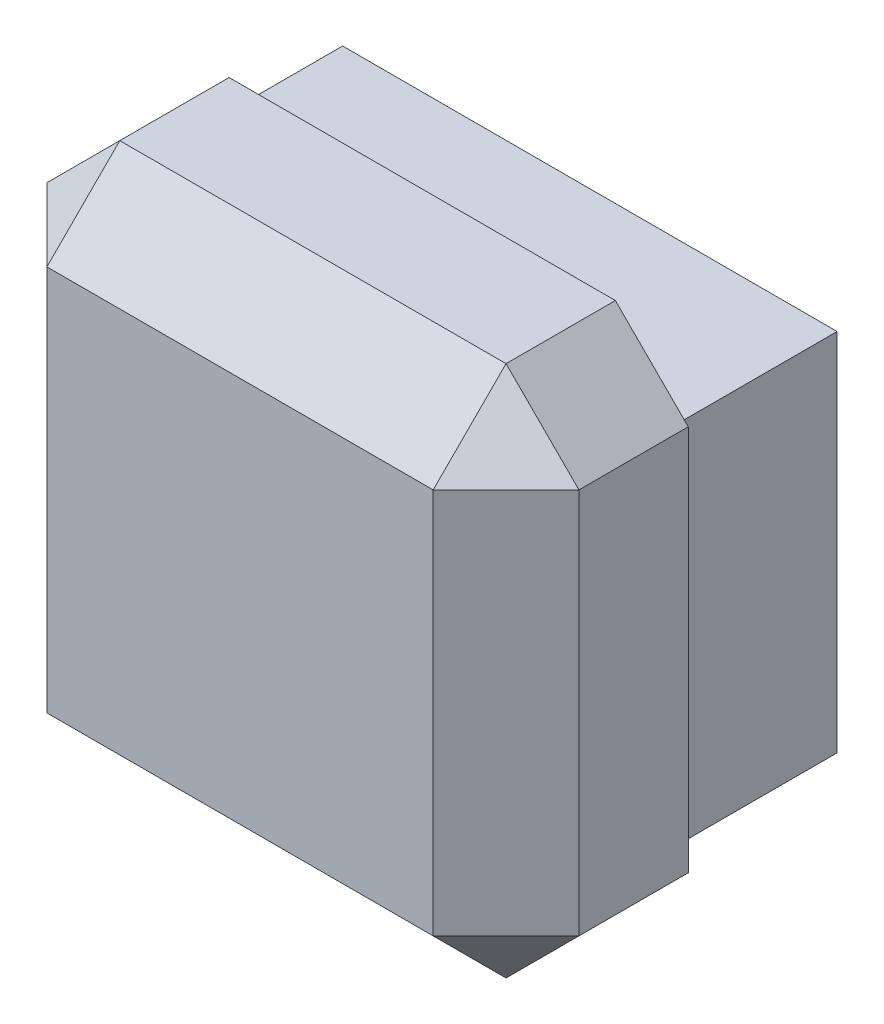
SolidWorks part; units mm, degrees
ref_plane "Front" through (0, 0, 0) normal (0, 0, 1) x (1, 0, 0)
ref_plane "Top" through (0, 0, 0) normal (0, 1, 0) x (1, 0, 0)
ref_plane "Right" through (0, 0, 0) normal (1, 0, 0) x (0, 0, -1)
sketch "Sketch1" plane through (0, 0, 0) normal (0, 0, 1) x (1, 0, 0)
  line L1 (-1.8923, -1.0033) -> (1.8923, -1.0033) construction
  line L2 (-1.8923, -1.0033) -> (-1.8923, 1.0033) construction
  line L3 (-1.8923, 1.0033) -> (1.8923, 1.0033) construction
  line L4 (1.8923, -1.0033) -> (1.8923, 1.0033) construction
  line L5 (-3.3923, -2.5033) -> (3.3923, -2.5033)
  line L6 (-3.3923, -2.5033) -> (-3.3923, 2.5033)
  line L7 (-3.3923, 2.5033) -> (3.3923, 2.5033)
  line L8 (3.3923, -2.5033) -> (3.3923, 2.5033)
  line L9 (-3.3923, -2.5033) -> (3.3923, 2.5033) construction
  line L10 (-3.3923, 2.5033) -> (3.3923, -2.5033) construction
  line L11 (-1.9423, -1.0533) -> (1.9423, -1.0533)
  line L12 (-1.9423, -1.0533) -> (-1.9423, 1.0533)
  line L13 (-1.9423, 1.0533) -> (1.9423, 1.0533)
  line L14 (1.9423, -1.0533) -> (1.9423, 1.0533)
  line L15 (-1.9423, -1.0533) -> (1.9423, 1.0533) construction
  line L16 (-1.9423, 1.0533) -> (1.9423, -1.0533) construction
  point P6 (0, 0)
  point P12 (0, 0)
  dimension "D1" = 1.5
  dimension "D2" = 1.5
  dimension "D3" = 0.05
  dimension "D4" = 0.05
extrude "Boss-Extrude1" add sketch "Sketch1" against normal blind 2.3
sketch "Sketch2" plane through (0, 0, 0) normal (0, 0, 1) x (1, 0, 0)
  line L1 (-3.65, -3.65) -> (3.65, -3.65)
  line L2 (-3.65, -3.65) -> (-3.65, 3.65)
  line L3 (-3.65, 3.65) -> (3.65, 3.65)
  line L4 (3.65, -3.65) -> (3.65, 3.65)
  line L5 (-3.65, -3.65) -> (3.65, 3.65) construction
  line L6 (-3.65, 3.65) -> (3.65, -3.65) construction
  point P0 (0, 0)
  dimension "D1" = 7.3
extrude "Boss-Extrude2" add sketch "Sketch2" along normal blind 2.5
fillet "Fillet1" [suppressed] radius 2
chamfer "Chamfer1" distance 1 angle 45 8 edges at (0, -3.65, 2.5) (3.65, -3.65, 1.25) (3.65, 0, 2.5) (3.65, 3.65, 1.25) (0, 3.65, 2.5) (-3.65, 3.65, 1.25) (-3.65, 0, 2.5) (-3.65, -3.65, 1.25)
sketch "Sketch3" plane through (0, 0, 0) normal (0, 0, -1) x (-1, 0, 0)
  line L4 (1.9423, 1.0533) -> (-1.9423, 1.0533)
  line L5 (-1.9423, 1.0533) -> (-1.9423, -1.0533)
  line L6 (-1.9423, -1.0533) -> (1.9423, -1.0533)
  line L7 (1.9423, -1.0533) -> (1.9423, 1.0533)
  line L8 (1.9423, 1.0533) -> (-1.9423, 1.0533)
  line L9 (-1.9423, 1.0533) -> (-1.9423, -1.0533)
  line L10 (-1.9423, -1.0533) -> (1.9423, -1.0533)
  line L11 (1.9423, -1.0533) -> (1.9423, 1.0533)
  dimension "D1" = 0
extrude "Cut-Extrude1" cut sketch "Sketch3" against normal blind 1.1
